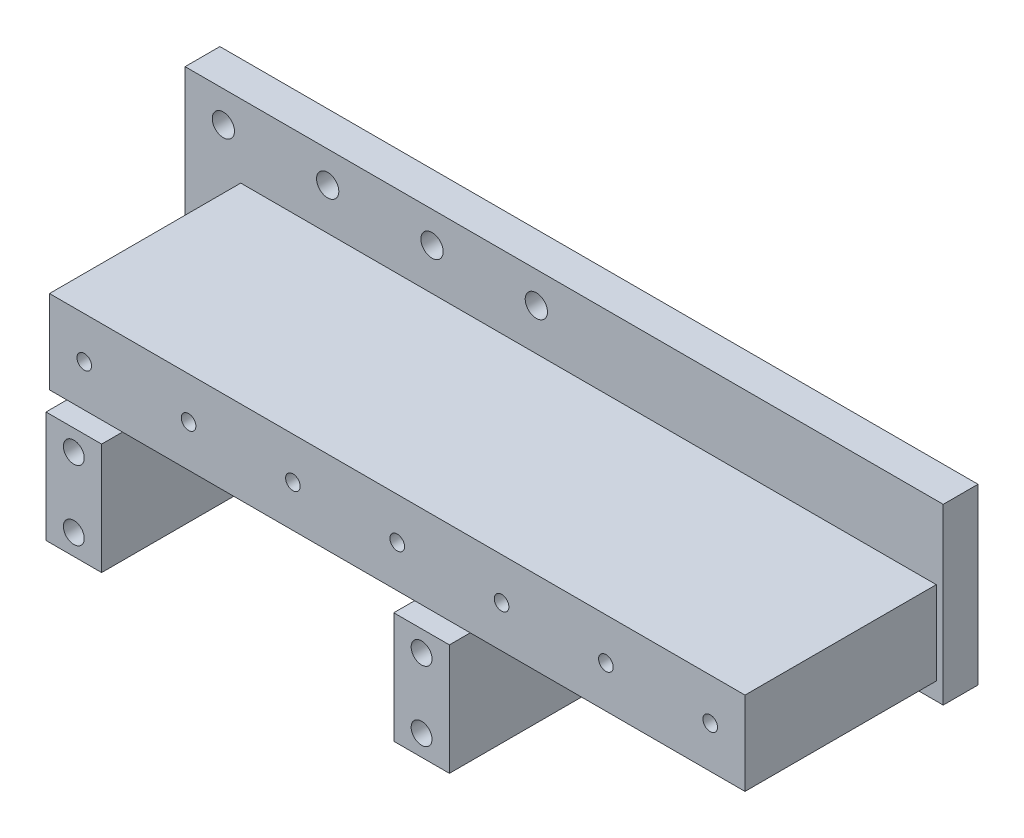
SolidWorks part; units mm, degrees
ref_plane "前视基准面" through (0, 0, 0) normal (0, 0, 1) x (1, 0, 0)
ref_plane "上视基准面" through (0, 0, 0) normal (0, 1, 0) x (1, 0, 0)
ref_plane "右视基准面" through (0, 0, 0) normal (1, 0, 0) x (0, 0, -1)
other "Configuration Table"
sketch "Base plate profile" plane through (0, 0, 0) normal (0, 0, 1) x (1, 0, 0)
  line L0 (-25, -15) -> (41, -15)
  line L1 (41, -15) -> (41, 10)
  line L2 (41, 10) -> (84, 10)
  line L3 (84, 10) -> (84, 35)
  line L4 (84, 35) -> (10, 35)
  line L8 (-10, 35) -> (-25, 35)
  line L9 (-25, 35) -> (-25, -15)
  line L10 (-10, 35) -> (10, 35)
extrude "Base plate" add sketch "Base plate profile" along normal blind 5 from offset 5
sketch "Mounting holes profile" plane through (0, 0, 0) normal (0, 0, 1) x (1, 0, 0)
  line L0 (84, 35) -> (-25, 35) construction
  circle A0 centre (-19.5, -10.5) radius 1.6
  circle A1 centre (-19.5, 30.5) radius 1.6
  circle A2 centre (25.5, -10.5) radius 1.6
  circle A3 centre (25.5, 30.5) radius 1.6
  circle A4 centre (-4.5, 30.5) radius 1.6
  circle A5 centre (10.5, 30.5) radius 1.6
  dimension "D1" = 4.5
  dimension "D2" = 3.2
  dimension "D3" = 3.2
  dimension "D4" = 3.2
  dimension "D5" = 3.2
  dimension "D6" = 45
  dimension "D7" = 41
  dimension "D8" = 4.5
  dimension "D9" = 4.5
  dimension "D10" = 15
  dimension "D11" = 15
  dimension "D12" = 3.2
  dimension "D13" = 3.2
extrude "Mounting holes" cut sketch "Mounting holes profile" along normal blind 5.3 from offset 5.1
sketch "Rail support profile" plane through (0, 0, 0) normal (0, 0, 1) x (1, 0, 0)
  line L0 (-17, 12.5) -> (83, 12.5)
  line L1 (83, 12.5) -> (83, 24.5)
  line L2 (83, 24.5) -> (-17, 24.5)
  line L3 (-17, 24.5) -> (-17, 12.5)
extrude "Rail support" add sketch "Rail support profile" along normal blind 27.5
sketch "Rail fasteners profile" plane through (0, 0, 0) normal (0, 0, 1) x (1, 0, 0)
  circle A0 centre (-12, 18.5) radius 1.05
  circle A1 centre (3, 18.5) radius 1.05
  circle A2 centre (18, 18.5) radius 1.05
  circle A3 centre (33, 18.5) radius 1.05
  circle A4 centre (48, 18.5) radius 1.05
  circle A5 centre (63, 18.5) radius 1.05
  circle A6 centre (78, 18.5) radius 1.05
extrude "Rail fasteners" cut sketch "Rail fasteners profile" along normal blind 6.6 from offset 21
sketch "Servo supports profile" plane through (0, 0, 0) normal (0, 0, 1) x (1, 0, 0)
  line L0 (-19, -8) -> (-11, -8)
  line L1 (-11, -8) -> (-11, 8)
  line L2 (-11, 8) -> (-19, 8)
  line L3 (-19, 8) -> (-19, -8)
  line L4 (31, -8) -> (39, -8)
  line L5 (39, -8) -> (39, 8)
  line L6 (39, 8) -> (31, 8)
  line L7 (31, 8) -> (31, -8)
extrude "Servo supports" add sketch "Servo supports profile" along normal blind 26
sketch "Servo fasteners profile" plane through (0, 0, 0) normal (0, 0, 1) x (1, 0, 0)
  circle A0 centre (-15, -5) radius 1.5
  circle A1 centre (-15, 5) radius 1.5
  circle A2 centre (35, -5) radius 1.5
  circle A3 centre (35, 5) radius 1.5
extrude "Servo fasteners" cut sketch "Servo fasteners profile" along normal blind 8.1 from offset 18
